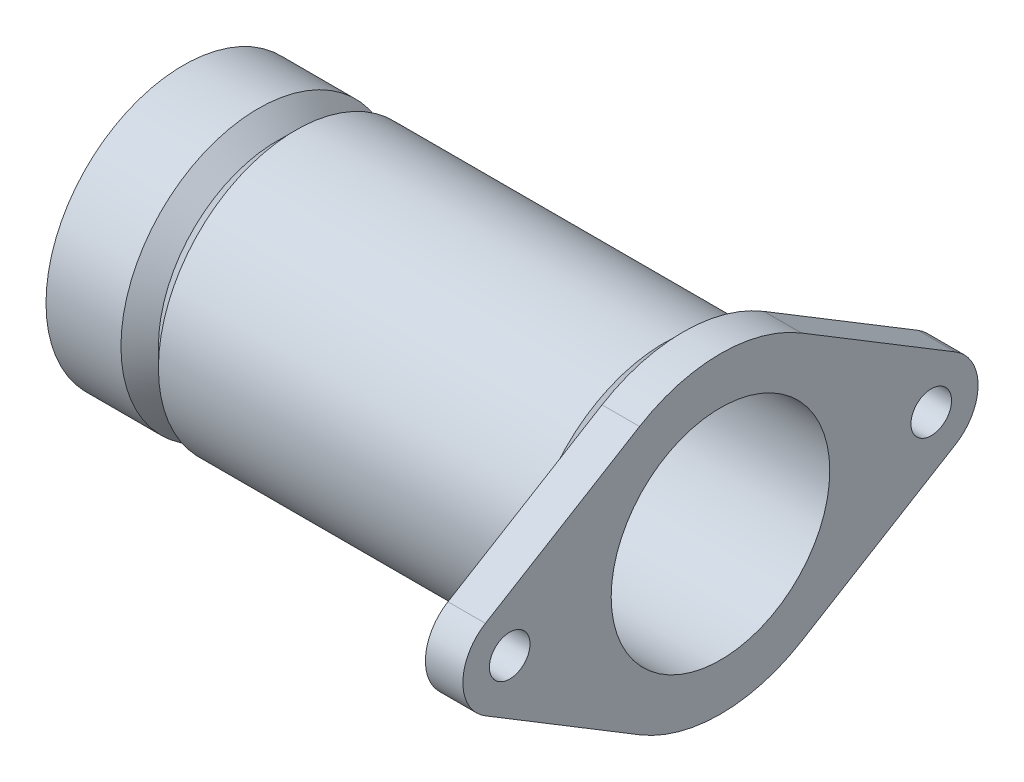
SolidWorks part; units mm, degrees
material "ASTM A36 Steel"
ref_plane "Front Plane" through (0, 0, 0) normal (0, 0, 1) x (1, 0, 0)
ref_plane "Top Plane" through (0, 0, 0) normal (0, 1, 0) x (1, 0, 0)
ref_plane "Right Plane" through (0, 0, 0) normal (1, 0, 0) x (0, 0, -1)
sketch "Sketch1" plane through (0, 0, 0) normal (1, 0, 0) x (0, 0, -1)
  circle A0 centre (0, 0) radius 44
  dimension "D1" = 88
extrude "Boss-Extrude1" add sketch "Sketch1" along normal blind 160
sketch "Sketch2" plane through (160, 0, 0) normal (1, 0, 0) x (0, 0, -1)
  line L0 (-25.9259, 42.7533) -> (-75.2778, 12.826)
  line L1 (25.9259, 42.7533) -> (75.2778, 12.826)
  line L2 (-75.2778, -12.826) -> (-25.9259, -42.7533)
  line L3 (75.2778, -12.826) -> (25.9259, -42.7533)
  arc A0 (25.9259, 42.7533) -> (-25.9259, 42.7533) centre (0, 0) ccw
  arc A1 (-75.2778, 12.826) -> (-75.2778, -12.826) centre (-67.5, 0) ccw
  arc A2 (75.2778, -12.826) -> (75.2778, 12.826) centre (67.5, 0) ccw
  arc A3 (-25.9259, -42.7533) -> (25.9259, -42.7533) centre (0, 0) ccw
  dimension "D1" = 100
  dimension "D2" = 30
  dimension "D3" = 30
  dimension "D4" = 67.5
  dimension "D5" = 67.5
extrude "Boss-Extrude2" add sketch "Sketch2" along normal blind 12
sketch "Sketch5" plane through (172, 0, 0) normal (1, 0, 0) x (0, 0, -1)
  circle A0 centre (67.5, 0) radius 6.5
  circle A1 centre (-67.5, 0) radius 6.5
  dimension "D1" = 13
  dimension "D2" = 13
extrude "Cut-Extrude3" cut sketch "Sketch5" against normal blind 80
sketch "Sketch6" plane through (172, 0, 0) normal (1, 0, 0) x (0, 0, -1)
  circle A0 centre (0, 0) radius 35
  dimension "D1" = 70
extrude "Cut-Extrude4" cut sketch "Sketch6" against normal blind 142
sketch "Sketch7" plane through (0, 0, 0) normal (-1, 0, 0) x (0, 0, 1)
  circle A0 centre (0, 0) radius 25.5
  dimension "D1" = 51
extrude "Cut-Extrude5" cut sketch "Sketch7" against normal blind 82
sketch "Sketch9" plane through (0, 0, 0) normal (0, 1, 0) x (1, 0, 0)
  line L0 (30, 38.0021) -> (24, 44.0021)
  line L1 (30, -35) -> (30, 35) construction
  line L2 (24, 44.0021) -> (36, 44.0021)
  line L3 (36, 44.0021) -> (30, 38.0021)
  line L4 (160, 44.0006) -> (160, 38.0006)
  line L5 (160, 44) -> (160, -44) construction
  line L6 (160, 25.9259) -> (160, 75.2778) construction
  line L7 (160, 38.0006) -> (154, 44.0006)
  line L8 (154, 44.0006) -> (160, 44.0006)
  line L9 (0, 0) -> (80.965, 0) construction
  dimension "D1" = 45
  dimension "D2" = 6
  dimension "D3" = 90
  dimension "D4" = 12
  dimension "D5" = 6
revolve "Cut-Revolve1" cut sketch "Sketch9" angle 360 about L9
